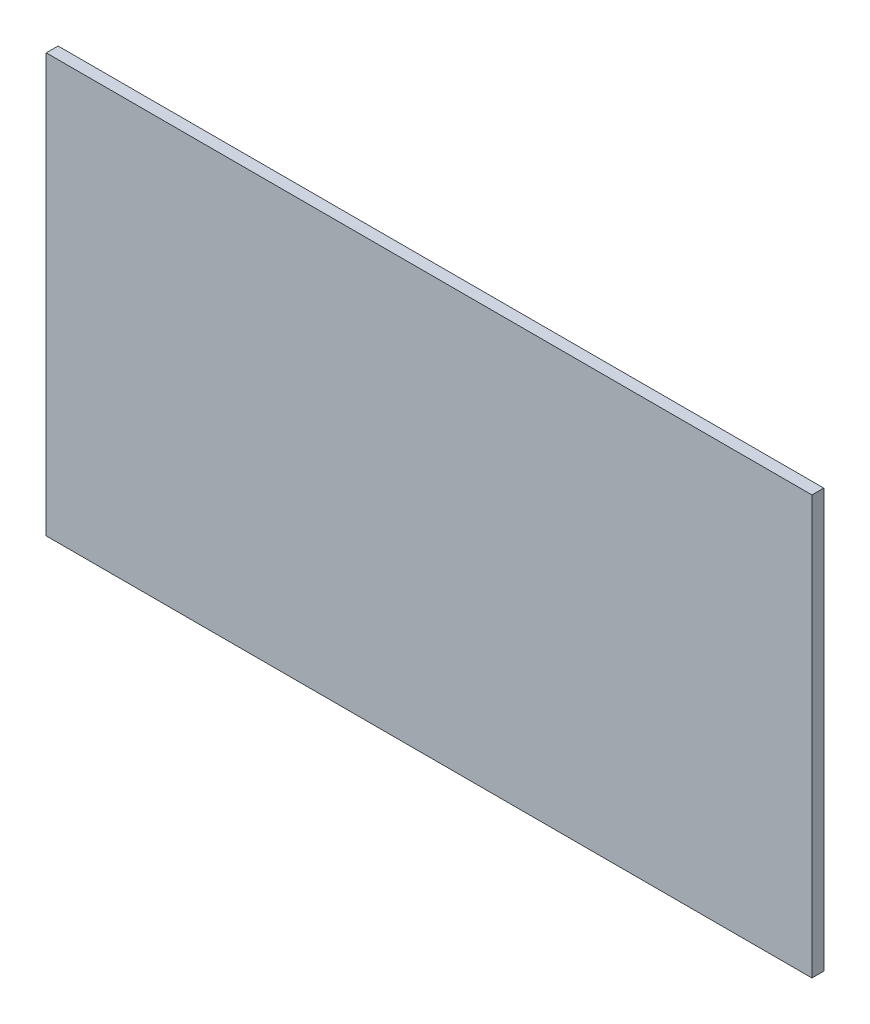
SolidWorks part; units mm, degrees
ref_plane "Front Plane" through (0, 0, 0) normal (0, 0, 1) x (1, 0, 0)
ref_plane "Top Plane" through (0, 0, 0) normal (0, 1, 0) x (1, 0, 0)
ref_plane "Right Plane" through (0, 0, 0) normal (1, 0, 0) x (0, 0, -1)
sketch "Sketch1" plane through (0, 0, 0) normal (0, 0, 1) x (1, 0, 0)
  line L1 (0, 0) -> (194, 0)
  line L2 (0, 0) -> (0, 106)
  line L3 (0, 106) -> (194, 106)
  line L4 (194, 0) -> (194, 106)
  dimension "D1" = 194
  dimension "D2" = 106
extrude "Profile" add sketch "Sketch1" along normal blind 3
equation "\"Profile_Depth\" = 3mm"
equation "\"D1@Profile\" = \"Profile_Depth\""
equation "\"EnvelopeWidth\" = 194mm"
equation "\"EnvelopeHeight\" = 106mm"
